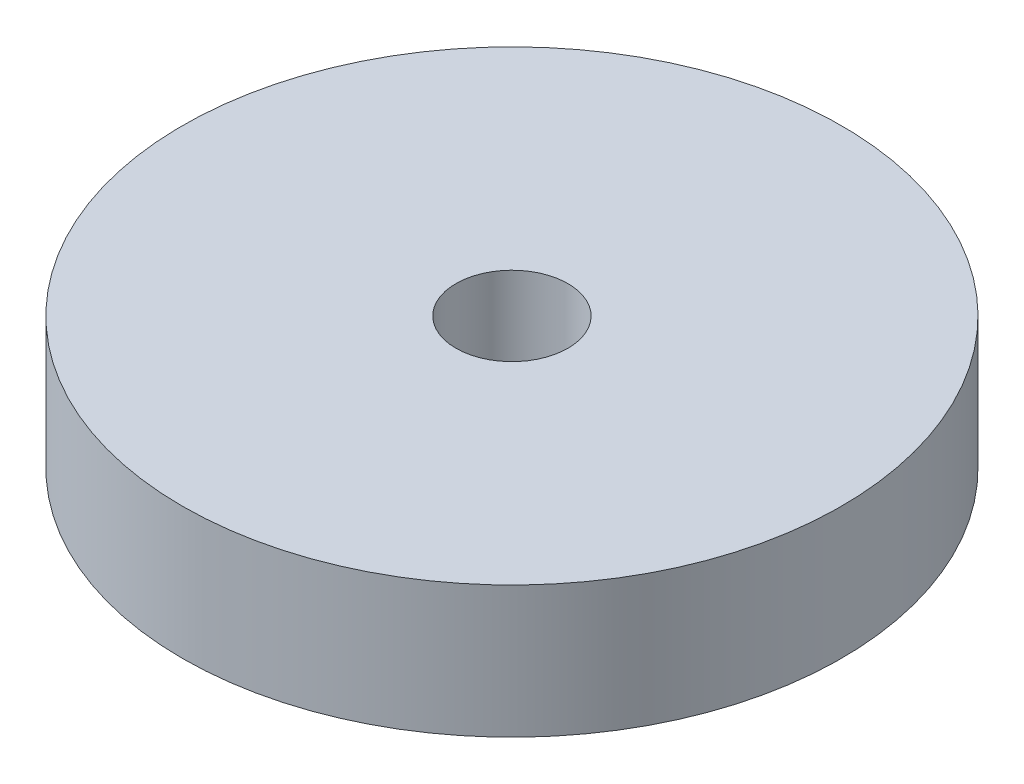
SolidWorks part; units mm, degrees
ref_plane "Front Plane" through (0, 0, 0) normal (0, 0, 1) x (1, 0, 0)
ref_plane "Top Plane" through (0, 0, 0) normal (0, 1, 0) x (1, 0, 0)
ref_plane "Right Plane" through (0, 0, 0) normal (1, 0, 0) x (0, 0, -1)
sketch "Sketch1" plane through (0, 0, 0) normal (0, 1, 0) x (1, 0, 0)
  circle A0 centre (0, 0) radius 4.25
  circle A1 centre (0, 0) radius 25
  dimension "D1" = 8.5
  dimension "D2" = 50
extrude "Boss-Extrude1" add sketch "Sketch1" along normal blind 10
